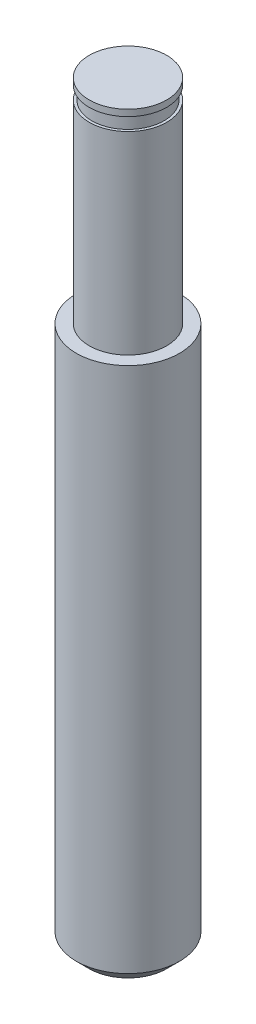
SolidWorks part; units mm, degrees
material "Alloy Steel"
ref_plane "Front" through (0, 0, 0) normal (0, 0, 1) x (1, 0, 0)
ref_plane "Top" through (0, 0, 0) normal (0, 1, 0) x (1, 0, 0)
ref_plane "Right" through (0, 0, 0) normal (1, 0, 0) x (0, 0, -1)
sketch "Sketch1" plane through (0, 0, 0) normal (0, 0, 1) x (1, 0, 0)
  line L0 (0, 29.15) -> (0, -29.15) construction
  line L1 (0, 29.15) -> (3, 29.15)
  line L2 (0, 29.15) -> (0, -29.15)
  line L3 (3, 29.15) -> (3, 28.65)
  line L4 (3, 28.65) -> (2.8, 28.65)
  line L5 (2.8, 28.65) -> (2.8, 27.65)
  line L6 (2.8, 27.65) -> (3, 27.65)
  line L7 (3, 27.65) -> (3, 12.65)
  line L8 (3, 12.65) -> (4, 12.65)
  line L9 (4, 12.65) -> (4, -29.15)
  line L10 (4, -29.15) -> (0, -29.15)
  dimension "D1" = 8
  dimension "D2" = 6
  dimension "D3" = 0.5
  dimension "D6" = 5.6
  dimension "D7" = 1
  dimension "D8" = 15
  dimension "D9" = 41.8
revolve "Revolve1" add sketch "Sketch1" angle 360 about L0
chamfer "Chamfer1" distance 1 angle 45 1 edges at (0, -29.15, 4)
